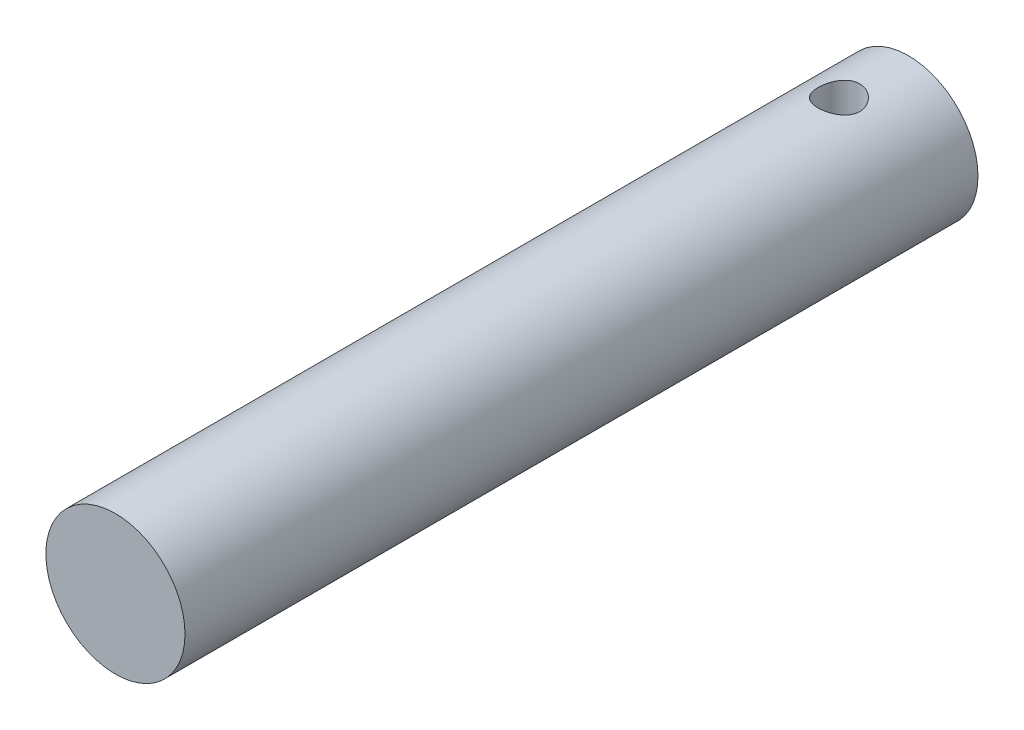
SolidWorks part; units mm, degrees
material "201 Annealed Stainless Steel (SS)"
ref_plane "Front Plane" through (0, 0, 0) normal (0, 0, 1) x (1, 0, 0)
ref_plane "Top Plane" through (0, 0, 0) normal (0, 1, 0) x (1, 0, 0)
ref_plane "Right Plane" through (0, 0, 0) normal (1, 0, 0) x (0, 0, -1)
sketch "Sketch2" plane through (0, 0, 0) normal (0, 0, 1) x (1, 0, 0)
  circle A0 centre (0, 0) radius 5
  dimension "D1" = 10
extrude "Boss-Extrude1" add sketch "Sketch2" along normal mid plane 57
cosmetic thread "Cosmetic Thread1" parameters "D1"=10, "D2"=8.344
sketch "Sketch3" plane through (0, 0, 0) normal (0, 1, 0) x (1, 0, 0)
  line L0 (0, 0) -> (0, 50000) construction
  line L1 (5, 28.5) -> (-5, 28.5) construction
  circle A0 centre (0, 23.5) radius 1.5
  dimension "D1" = 3
  dimension "D2" = 5
extrude "Cut-Extrude1" cut sketch "Sketch3" against normal through all both and the other way through all
